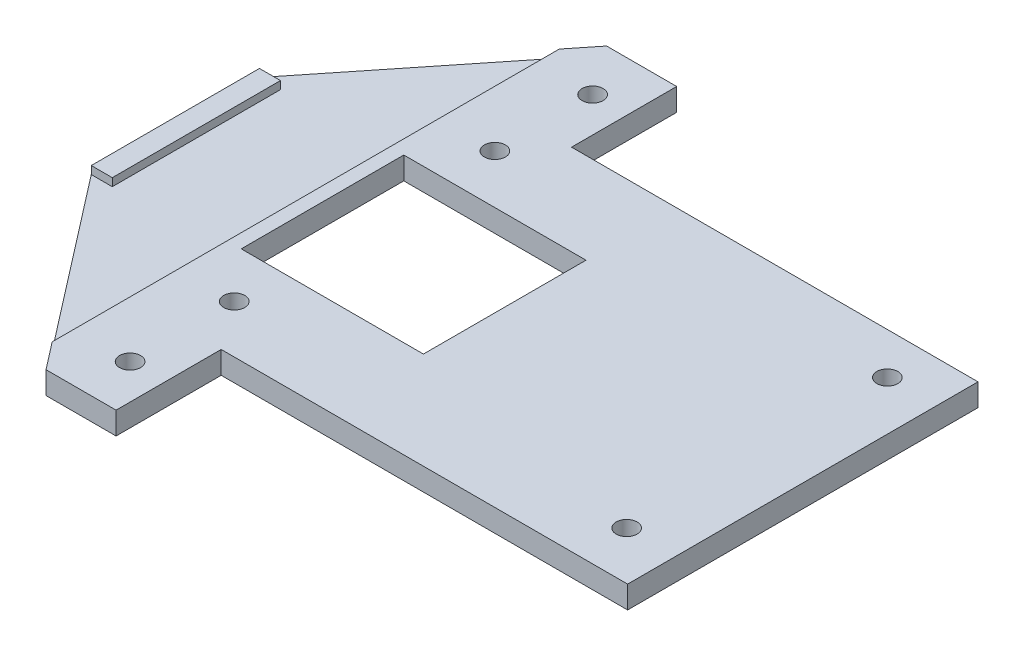
SolidWorks part; units mm, degrees
material "6061 Alloy"
ref_plane "Front Plane" through (0, 0, 0) normal (0, 0, 1) x (1, 0, 0)
ref_plane "Top Plane" through (0, 0, 0) normal (0, 1, 0) x (1, 0, 0)
ref_plane "Right Plane" through (0, 0, 0) normal (1, 0, 0) x (0, 0, -1)
sketch "Sketch1" plane through (0, 0, 0) normal (0, 1, 0) x (1, 0, 0)
  line L0 (0, 6) -> (0, -6)
  line L1 (0, -6) -> (11, -20.23)
  line L2 (11, -20.23) -> (16, -20.23)
  line L3 (16, -20.23) -> (16, -12.73)
  line L4 (16, -12.73) -> (45, -12.73)
  line L5 (45, -12.73) -> (45, 12.27)
  line L6 (45, 12.27) -> (16, 12.27)
  line L7 (16, 12.27) -> (16, 19.77)
  line L8 (16, 19.77) -> (11, 19.77)
  line L9 (11, 19.77) -> (0, 6)
  point P12 (0, 0)
  dimension "D1" = 12
  dimension "D2" = 5
  dimension "D3" = 11
  dimension "D4" = 13.77
  dimension "D5" = 40
  dimension "D6" = 7.5
  dimension "D7" = 7.5
  dimension "D8" = 45
extrude "Boss-Extrude1" add sketch "Sketch1" along normal blind 1.6
sketch "Sketch2" plane through (0, 1.6, 0) normal (0, 1, 0) x (1, 0, 0)
  line L0 (0, -6) -> (9.5, -18.2895)
  line L1 (0, 6) -> (1.5, 6)
  line L2 (0, 6) -> (0, -6) construction
  line L3 (0, -6) -> (1.5, -6)
  line L4 (1.5, 6) -> (1.5, -6)
  line L5 (0, -6) -> (11, -20.23) construction
  line L6 (9.5, -18.2895) -> (9.5, 17.8923)
  line L7 (11, 19.77) -> (0, 6) construction
  line L8 (9.5, 17.8923) -> (0, 6)
  dimension "D1" = 1.5
  dimension "D3" = 8
extrude "Cut-Extrude1" cut sketch "Sketch2" against normal blind 0.56
sketch "Sketch3" plane through (0, 1.6, 0) normal (0, 1, 0) x (1, 0, 0)
  line L0 (9.5, -18.2895) -> (9.5, 17.8923) construction
  line L1 (10.5, 5.8) -> (23.5, 5.8)
  line L2 (10.5, 5.8) -> (10.5, -5.8)
  line L3 (10.5, -5.8) -> (23.5, -5.8)
  line L4 (23.5, 5.8) -> (23.5, -5.8)
  point P4 (10.5, 0)
  dimension "D1" = 1
  dimension "D2" = 11.6
  dimension "D3" = 13
extrude "Cut-Extrude2" cut sketch "Sketch3" against normal blind 2
sketch "Sketch4" plane through (0, 1.6, 0) normal (0, 1, 0) x (1, 0, 0)
  line L0 (16, 12.27) -> (16, 19.77) construction
  line L1 (16, 19.77) -> (11, 19.77) construction
  line L2 (23.5, 5.8) -> (10.5, 5.8) construction
  line L3 (10.5, -5.8) -> (23.5, -5.8) construction
  line L4 (11, -20.23) -> (16, -20.23) construction
  line L5 (45, -12.73) -> (45, 12.27) construction
  circle A0 centre (13.5, 16.27) radius 0.75
  circle A1 centre (13.5, 9.3) radius 0.75
  circle A2 centre (41.5, 9.3) radius 0.75
  circle A3 centre (41.5, -9.3) radius 0.75
  circle A4 centre (13.5, -9.3) radius 0.75
  circle A5 centre (13.5, -16.73) radius 0.75
  dimension "D7" = 1.5
  dimension "D1" = 2.5
  dimension "D2" = 3.5
  dimension "D3" = 3.5
  dimension "D4" = 3.5
  dimension "D5" = 3.5
  dimension "D6" = 3.5
extrude "Cut-Extrude3" cut sketch "Sketch4" against normal blind 2
